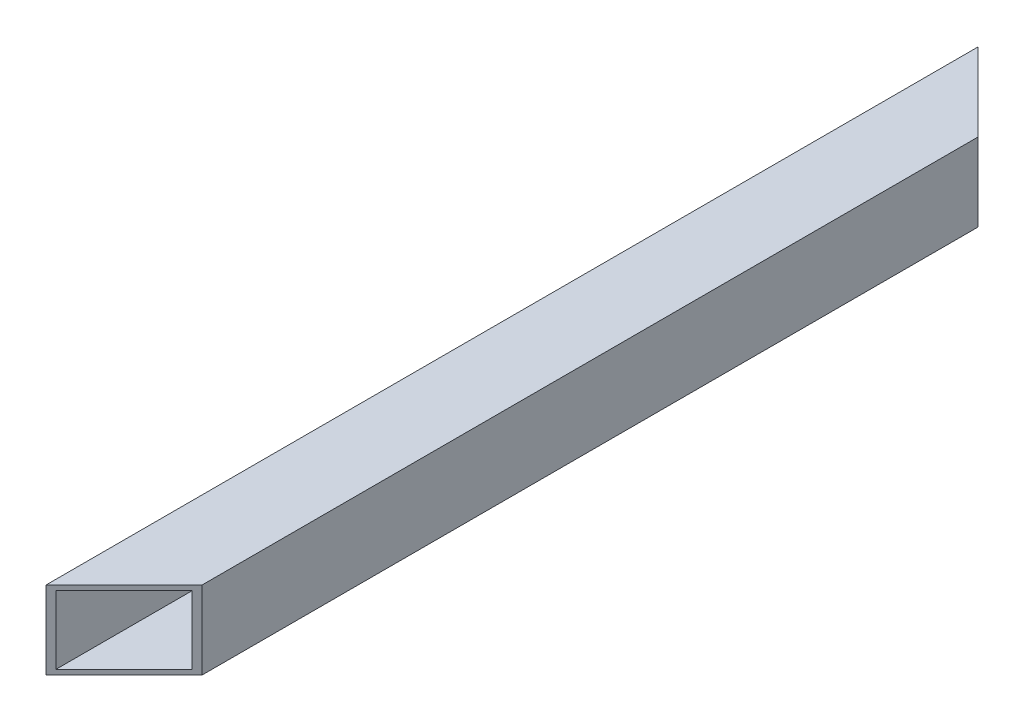
SolidWorks part; units mm, degrees
ref_plane "Front Plane" through (0, 0, 0) normal (0, 0, 1) x (1, 0, 0)
ref_plane "Top Plane" through (0, 0, 0) normal (0, 1, 0) x (1, 0, 0)
ref_plane "Right Plane" through (0, 0, 0) normal (1, 0, 0) x (0, 0, -1)
sketch "Sketch1" plane through (0, 0, 0) normal (0, 0, 1) x (1, 0, 0)
  line L0 (8.3, 8.3) -> (-8.3, 8.3)
  line L1 (9.5, 9.5) -> (-9.5, 9.5)
  line L2 (9.5, 9.5) -> (9.5, -9.5)
  line L3 (9.5, -9.5) -> (-9.5, -9.5)
  line L4 (-9.5, 9.5) -> (-9.5, -9.5)
  line L5 (9.5, 9.5) -> (-9.5, -9.5) construction
  line L6 (9.5, -9.5) -> (-9.5, 9.5) construction
  line L7 (-8.3, 8.3) -> (-8.3, -8.3)
  line L8 (8.3, -8.3) -> (-8.3, -8.3)
  line L9 (8.3, 8.3) -> (8.3, -8.3)
  point P0 (0, 0)
  dimension "D1" = 19
  dimension "D2" = 1.2
extrude "Boss-Extrude1" add sketch "Sketch1" along normal mid plane 226.98
sketch "Sketch2" plane through (0, 9.5, 0) normal (0, 1, 0) x (1, 0, 0)
  line L0 (-9.5, -113.49) -> (9.5, -113.49)
  line L1 (9.5, -113.49) -> (9.5, -94.49)
  line L2 (9.5, -113.49) -> (9.5, 113.49) construction
  line L3 (9.5, -94.49) -> (-9.5, -113.49)
  line L4 (-9.5, 113.49) -> (9.5, 113.49)
  line L5 (9.5, 113.49) -> (9.5, 94.49)
  line L6 (9.5, 94.49) -> (-9.5, 113.49)
extrude "Cut-Extrude1" cut sketch "Sketch2" against normal through all
